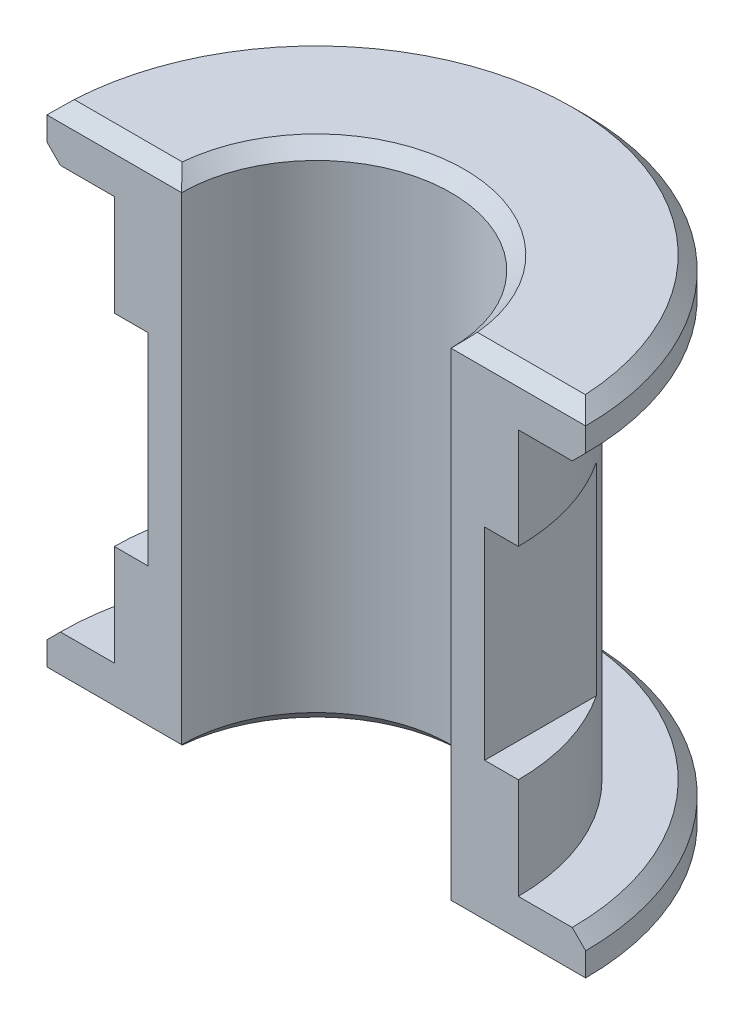
SolidWorks part; units mm, degrees
ref_plane "前视基准面" through (0, 0, 0) normal (0, 0, 1) x (1, 0, 0)
ref_plane "上视基准面" through (0, 0, 0) normal (0, 1, 0) x (1, 0, 0)
ref_plane "右视基准面" through (0, 0, 0) normal (1, 0, 0) x (0, 0, -1)
sketch "草图1" plane through (0, 0, 0) normal (0, 0, 1) x (1, 0, 0)
  line L0 (0, 37.5) -> (0, -37.5)
  line L1 (0, -37.5) -> (40, -37.5)
  line L2 (40, -37.5) -> (40, -30)
  line L3 (40, -30) -> (30, -30)
  line L4 (30, -30) -> (30, 30)
  line L5 (30, 30) -> (40, 30)
  line L6 (40, 30) -> (40, 37.5)
  line L7 (40, 37.5) -> (0, 37.5)
  line L8 (0, 37.5) -> (0, -37.5) construction
revolve "旋转1" add sketch "草图1" angle 180 about L8
ref_plane "基准面4" through (0, -15, 0) normal (0, -1, 0) x (1, 0, 0)
sketch "草图2" plane through (0, -15, 0) normal (0, -1, 0) x (1, 0, 0)
  line L0 (25, 0) -> (25, -16.5831)
  line L1 (30, 0) -> (25, 0)
  arc A0 (25, -16.5831) -> (30, 0) centre (0, 0) ccw
extrude "切除-拉伸1" cut sketch "草图2" against normal blind 30
sketch "草图3" plane through (0, -15, 0) normal (0, -1, 0) x (1, 0, 0)
  line L0 (-25, -16.5831) -> (-25, 0)
  line L1 (-25, 0) -> (-30, 0)
  arc A0 (-30, 0) -> (-25, -16.5831) centre (0, 0) ccw
extrude "切除-拉伸2" cut sketch "草图3" against normal blind 30
hole_wizard "M39 螺旋的螺纹孔钻头1" positions "草图5" profile "草图4" hole size "M39x3.0" standard "ANSI Metric"
sketch "草图5" plane through (0, 37.5, 0) normal (0, 1, 0) x (1, 0, 0)
  point P0 (0, 0)
sketch "草图4" plane through (0, 37.5, 0) normal (1, 0, 0) x (0, 0, 1)
  line L0 (0, 0) -> (0, 75)
  line L1 (0, 75) -> (20, 75)
  line L2 (20, 75) -> (20, 0)
  line L5 (20, 0) -> (0, 0)
  line L11 (0, -6.35) -> (0, 107.95) construction
  dimension "通孔孔直径" = 40
  dimension "通孔孔深度" = 75
chamfer "倒角1" distance 2 angle 45 10 edges at (30, 37.5, 0) (-30, 37.5, 0) (0, 37.5, -20) (0, 37.5, -40) (-30, -37.5, 0) (30, -37.5, 0) (0, -37.5, -20) (0, -37.5, -40) (0, -30, -40) (0, 30, -40)
